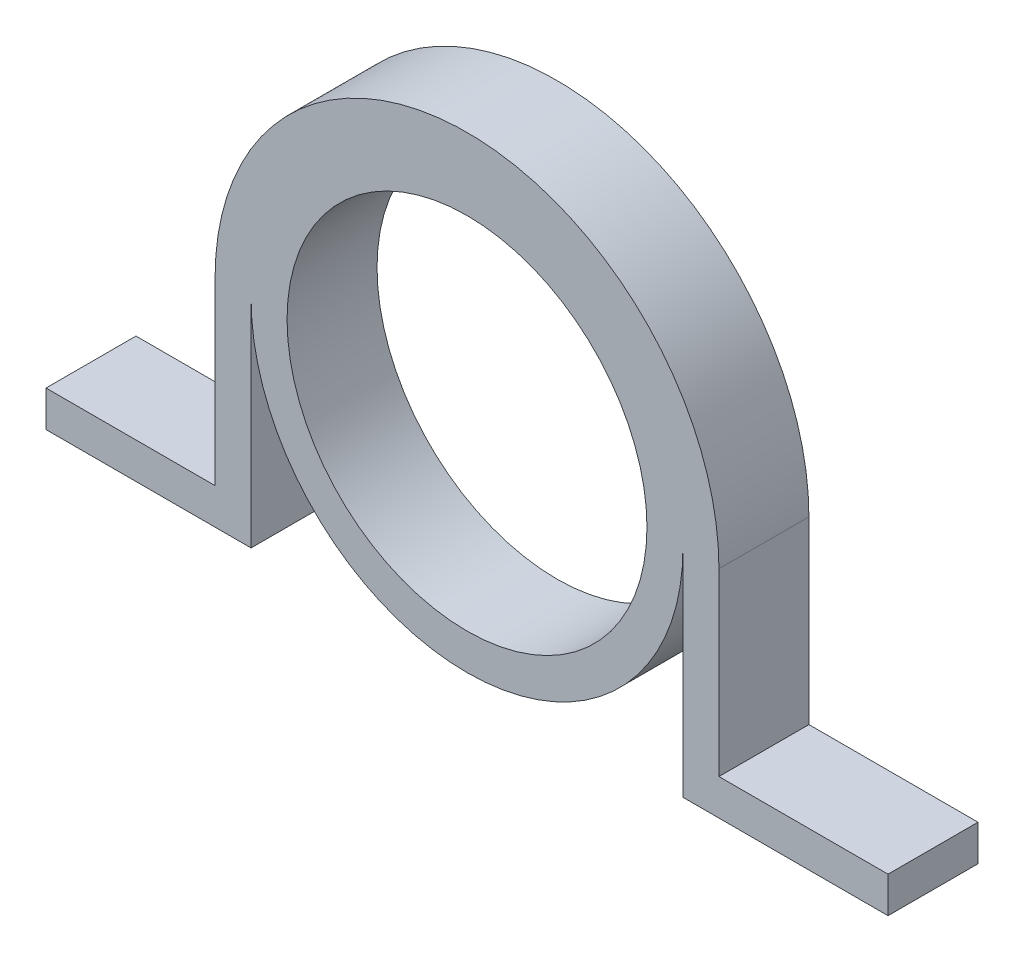
SolidWorks part; units mm, degrees
ref_plane "Front Plane" through (0, 0, 0) normal (0, 0, 1) x (1, 0, 0)
ref_plane "Top Plane" through (0, 0, 0) normal (0, 1, 0) x (1, 0, 0)
ref_plane "Right Plane" through (0, 0, 0) normal (1, 0, 0) x (0, 0, -1)
sketch "Sketch1" plane through (0, 0, 0) normal (0, 0, 1) x (1, 0, 0)
  line L0 (-46.5499, 0) -> (46.5499, 0) construction
  line L1 (-12, 0) -> (-12, -12)
  line L4 (-12, -12) -> (-23.3953, -12)
  line L5 (-23.3953, -12) -> (-23.3953, -10)
  line L6 (-23.3953, -10) -> (-14, -10)
  line L7 (-14, -10) -> (-14, 0)
  line L8 (0, 0) -> (0, 15.0242) construction
  line L9 (12, -12) -> (23.3953, -12)
  line L10 (23.3953, -12) -> (23.3953, -10)
  line L11 (23.3953, -10) -> (14, -10)
  line L12 (14, -10) -> (14, 0)
  line L13 (12, 0) -> (12, -12)
  circle A0 centre (0, 0) radius 10
  circle A1 centre (0, 0) radius 12
  arc A4 (14, 0) -> (-14, 0) centre (0, 0) ccw
  circle A5 centre (0, 0) radius 14 construction
  point P7 (0, 0)
  dimension "D4" = 2
  dimension "D5" = 2
extrude "Boss-Extrude1" add sketch "Sketch1" along normal blind 5 contours L12 A4 L7 L6 L5 L4 L1 A1 L13 L9 L10 L11 | A1 A0
